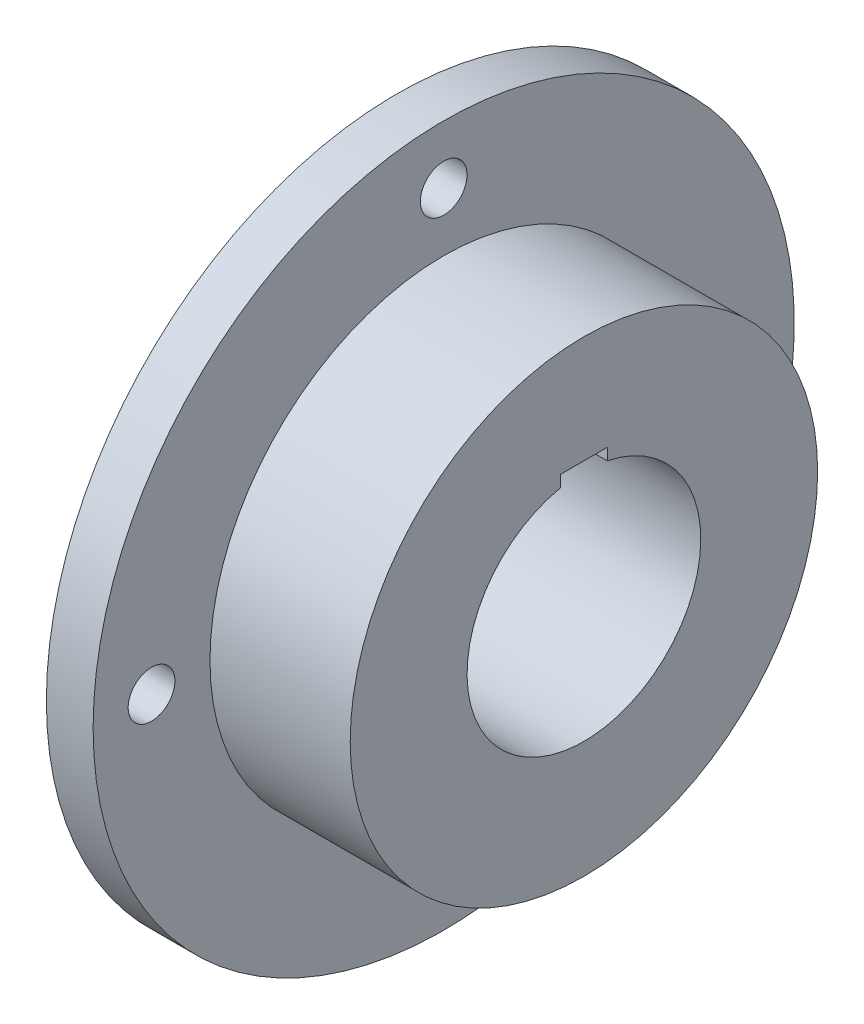
SolidWorks part; units mm, degrees
material "2024-T4"
ref_plane "Front Plane" through (0, 0, 0) normal (0, 0, 1) x (1, 0, 0)
ref_plane "Top Plane" through (0, 0, 0) normal (0, 1, 0) x (1, 0, 0)
ref_plane "Right Plane" through (0, 0, 0) normal (1, 0, 0) x (0, 0, -1)
sketch "Sketch1" plane through (0, 0, 0) normal (1, 0, 0) x (0, 0, -1)
  circle A0 centre (0, 0) radius 10
  circle A1 centre (0, 0) radius 20
  dimension "D1" = 20
  dimension "D2" = 40
extrude "Boss-Extrude1" add sketch "Sketch1" along normal mid plane 14
sketch "Sketch2" plane through (-7, 0, 0) normal (-1, 0, 0) x (0, 0, 1)
  circle A0 centre (0, 0) radius 30
  circle A1 centre (0, 0) radius 10 construction
  circle A2 centre (0, 0) radius 10
  dimension "D1" = 60
extrude "Boss-Extrude2" add sketch "Sketch2" along normal mid plane 4
sketch "Sketch3" plane through (-5, 0, 0) normal (1, 0, 0) x (0, 0, -1)
  line L0 (0, 0) -> (0, 25) construction
  circle A0 centre (0, 25) radius 2
  circle A1 centre (0, 0) radius 25 construction
  circle A2 centre (25, 0) radius 2
  circle A3 centre (0, -25) radius 2
  circle A4 centre (-25, 0) radius 2
  point P14 (0, 0)
  dimension "D1" = 4
  dimension "D2" = 50
  dimension "D4" = 25
  dimension "D5" = 25
  dimension "D3" = 4
extrude "Cut-Extrude1" cut sketch "Sketch3" against normal through all
sketch "Sketch4" plane through (7, 0, 0) normal (1, 0, 0) x (0, 0, -1)
  line L0 (0, 0) -> (0, 17.0623) construction
  line L1 (2, 10.798) -> (-2, 10.798)
  line L2 (-2, 10.798) -> (-2, 9.798)
  line L3 (2, 10.798) -> (2, 9.798)
  circle A0 centre (0, 0) radius 10 construction
  circle A1 centre (0, 0) radius 10
  point P10 (0, 10.798)
  circle M5 centre (0, 0) radius 10
  dimension "D1" = 1
  dimension "D2" = 2
extrude "Cut-Extrude2" cut sketch "Sketch4" against normal through all contours L0 L1 L2 M5 | L0 A1 L3 L1
equation "\"shaft-diameter\" =20mm"
equation "\"D1@Sketch1\"=\"shaft-diameter\""
